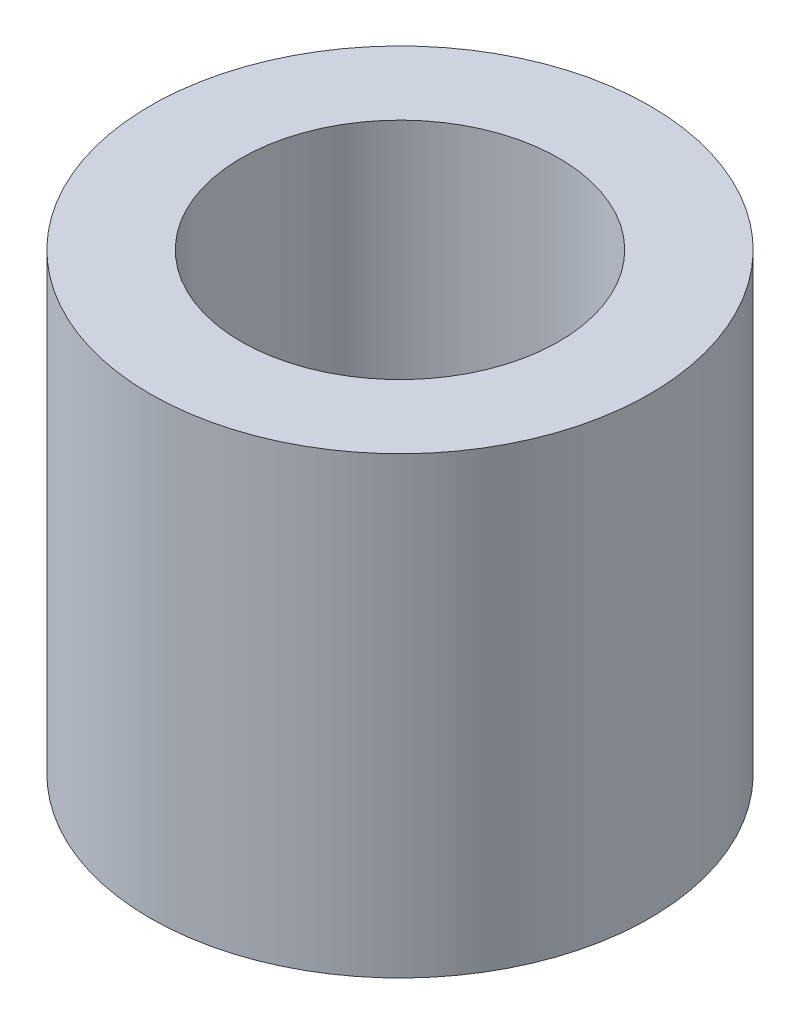
SolidWorks part; units mm, degrees
ref_plane "Plan de face" through (0, 0, 0) normal (0, 0, 1) x (1, 0, 0)
ref_plane "Plan de dessus" through (0, 0, 0) normal (0, 1, 0) x (1, 0, 0)
ref_plane "Plan de droite" through (0, 0, 0) normal (1, 0, 0) x (0, 0, -1)
sketch "Esquisse1" plane through (0, 0, 0) normal (0, 1, 0) x (1, 0, 0)
  circle A0 centre (0, 0) radius 3.5
  circle A1 centre (0, 0) radius 5.5
  dimension "D1" = 7
  dimension "D2" = 11
extrude "Boss.-Extru.1" add sketch "Esquisse1" along normal blind 10
